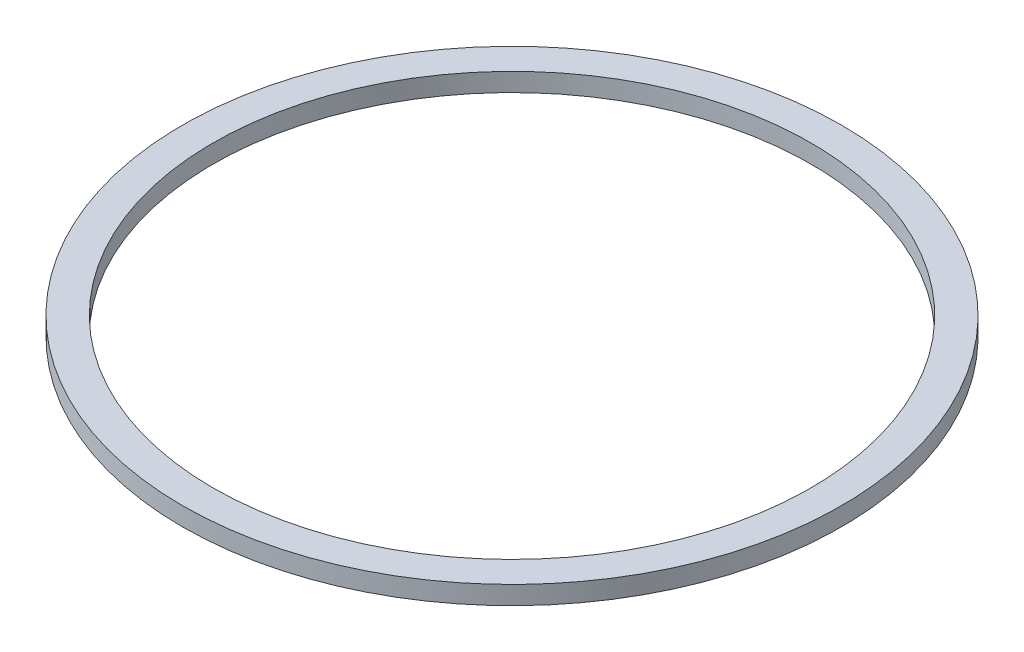
SolidWorks part; units mm, degrees
ref_plane "前视基准面" through (0, 0, 0) normal (0, 0, 1) x (1, 0, 0)
ref_plane "上视基准面" through (0, 0, 0) normal (0, 1, 0) x (1, 0, 0)
ref_plane "右视基准面" through (0, 0, 0) normal (1, 0, 0) x (0, 0, -1)
sketch "草图1" plane through (0, 0, 0) normal (0, 1, 0) x (1, 0, 0)
  circle A0 centre (0, 0) radius 19.5
  circle A1 centre (0, 0) radius 21.5
  circle A2 centre (0, 0) radius 21 construction
  dimension "D1" = 42
  dimension "D2" = 43
  dimension "D3" = 39
extrude "凸台-拉伸1" add sketch "草图1" along normal blind 1.2
